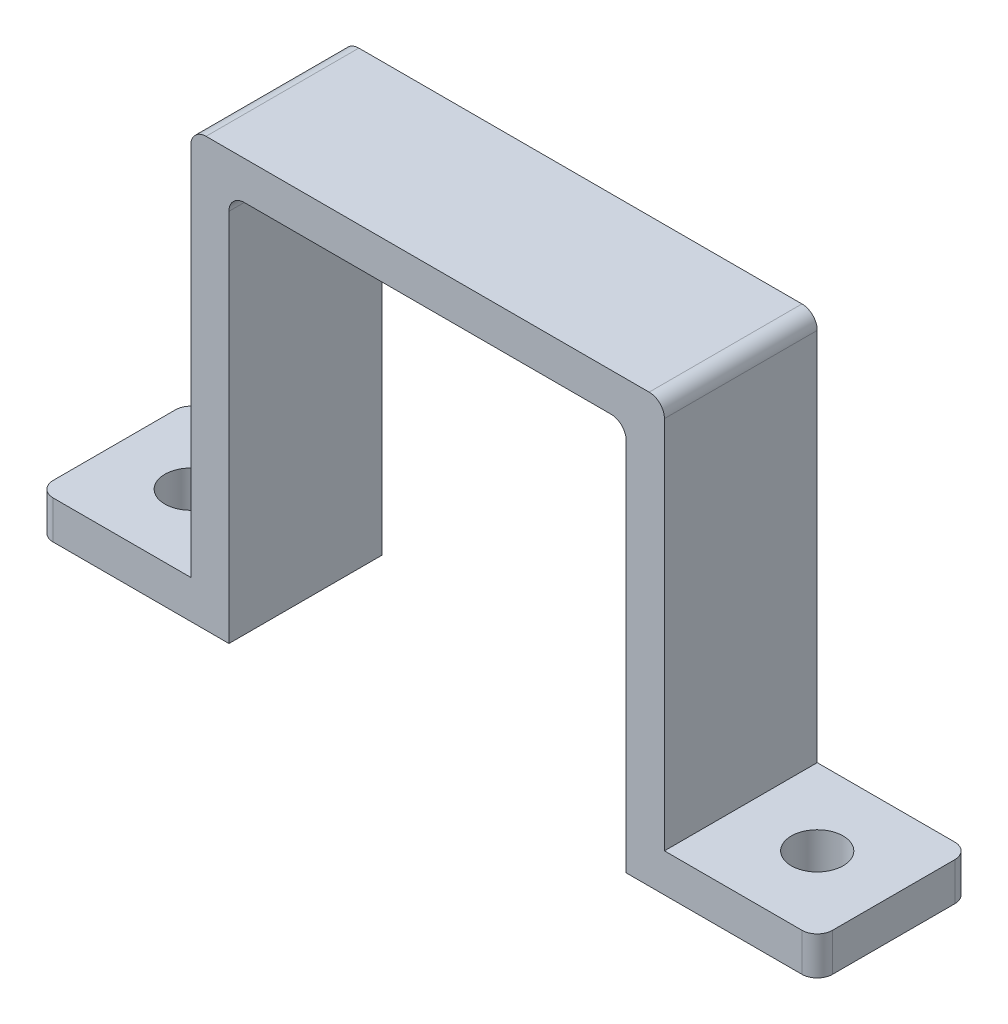
SolidWorks part; units mm, degrees
ref_plane "Front Plane" through (0, 0, 0) normal (0, 0, 1) x (1, 0, 0)
ref_plane "Top Plane" through (0, 0, 0) normal (0, 1, 0) x (1, 0, 0)
ref_plane "Right Plane" through (0, 0, 0) normal (1, 0, 0) x (0, 0, -1)
sketch "Sketch1" plane through (0, 0, 0) normal (0, 0, 1) x (1, 0, 0)
  line L0 (-15.875, 0) -> (0, 0)
  line L1 (0, 0) -> (0, 32.385)
  line L2 (0, 32.385) -> (33.02, 32.385)
  line L3 (33.02, 32.385) -> (33.02, 0)
  line L4 (33.02, 0) -> (48.895, 0)
  line L5 (48.895, 0) -> (48.895, 3.175)
  line L6 (48.895, 3.175) -> (36.195, 3.175)
  line L7 (36.195, 3.175) -> (36.195, 35.56)
  line L8 (36.195, 35.56) -> (-3.175, 35.56)
  line L9 (-3.175, 35.56) -> (-3.175, 3.175)
  line L10 (-3.175, 3.175) -> (-15.875, 3.175)
  line L11 (-15.875, 3.175) -> (-15.875, 0)
  point P12 (-3.5494, 37.0218)
  point P14 (-18.1762, 5.2688)
  dimension "D1" = 33.02
  dimension "D2" = 32.385
  dimension "D3" = 12.7
  dimension "wallthickness" = 3.175
  dimension "D5" = 3.175
  dimension "D6" = 3.175
extrude "Boss-Extrude1" add sketch "Sketch1" along normal blind 12.7
hole_wizard "#6 Clearance Hole1" positions "Sketch2" profile "Sketch3" hole size "#6" standard "ANSI Inch" end condition through all
sketch "Sketch2" plane through (0, 3.175, 0) normal (0, 1, 0) x (1, 0, 0)
  line L0 (-3.175, 0) -> (-15.875, 0) construction
  line L1 (-9.525, 0) -> (-9.525, -6.35) construction
  line L2 (-9.525, -6.35) -> (-15.875, -6.35) construction
  line L3 (-15.875, -12.7) -> (-15.875, 0) construction
  line L6 (42.545, 0) -> (42.545, -6.35) construction
  line L7 (48.895, 0) -> (36.195, 0) construction
  point P0 (-9.525, -6.35)
  point P2 (42.545, -6.35)
  point P23 (0, 0)
sketch "Sketch3" plane through (-9.525, 3.175, 6.35) normal (1, 0, 0) x (0, 0, 1)
  line L0 (0, 0) -> (0, 3.175)
  line L1 (0, 3.175) -> (2.1526, 3.175)
  line L2 (2.1526, 3.175) -> (2.1526, 0)
  line L5 (2.1526, 0) -> (0, 0)
  line L11 (0, -6.35) -> (0, 107.95) construction
  dimension "Thru Hole Dia." = 4.3053
  dimension "Thru Hole Depth" = 3.175
fillet "Fillet1" radius 1.27 8 edges at (-15.875, 1.5875, 0) (-15.875, 1.5875, 12.7) (48.895, 1.5875, 0) (48.895, 1.5875, 12.7) (36.195, 35.56, 6.35) (33.02, 32.385, 6.35) (0, 32.385, 6.35) (-3.175, 35.56, 6.35)
equation "\"D6@Sketch1\"=\"wallthickness@Sketch1\""
equation "\"D5@Sketch1\"=\"wallthickness@Sketch1\""
